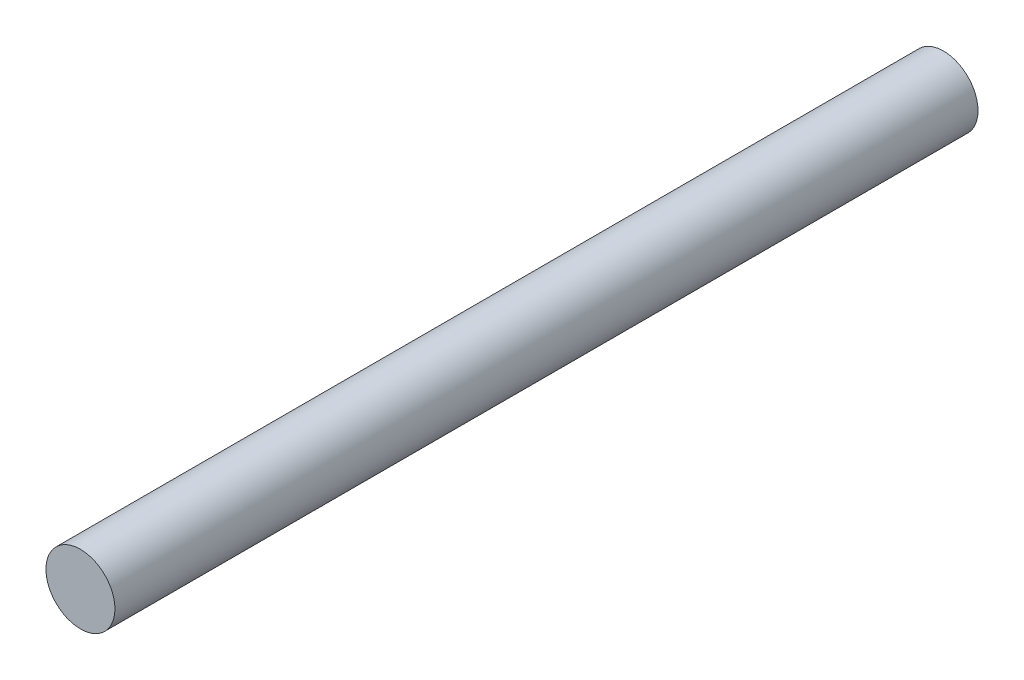
SolidWorks part; units mm, degrees
ref_plane "Front Plane" through (0, 0, 0) normal (0, 0, 1) x (1, 0, 0)
ref_plane "Top Plane" through (0, 0, 0) normal (0, 1, 0) x (1, 0, 0)
ref_plane "Right Plane" through (0, 0, 0) normal (1, 0, 0) x (0, 0, -1)
sketch "Sketch1" plane through (0, 0, 0) normal (0, 0, 1) x (1, 0, 0)
  circle A0 centre (0, 0) radius 6.35
  dimension "D1" = 12.7
extrude "Boss-Extrude1" add sketch "Sketch1" along normal blind 158.877
